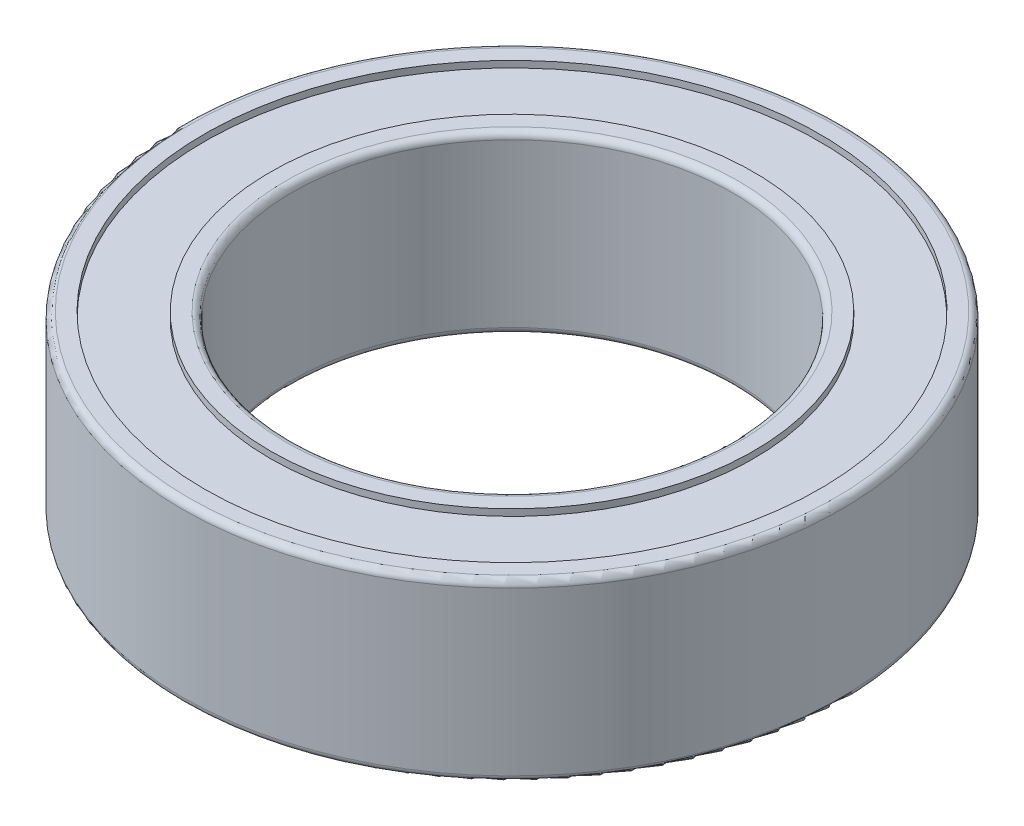
SolidWorks part; units mm, degrees
ref_plane "Plan de face" through (0, 0, 0) normal (0, 0, 1) x (1, 0, 0)
ref_plane "Plan de dessus" through (0, 0, 0) normal (0, 1, 0) x (1, 0, 0)
ref_plane "Plan de droite" through (0, 0, 0) normal (1, 0, 0) x (0, 0, -1)
ref_plane "Plan1" through (0, 0, 0) normal (0, 0, -1) x (-1, 0, 0)
sketch "Esquisse1" plane through (0, 0, 0) normal (0, 0, -1) x (-1, 0, 0)
  line L0 (-5, -1.85) -> (-5, 1.85)
  line L1 (-5.15, 2) -> (-5.5, 2)
  line L2 (-5.5, 2) -> (-5.5, 1.85)
  line L3 (-5.5, 1.85) -> (-7, 1.85)
  line L4 (-7, 1.85) -> (-7, 2)
  line L5 (-7, 2) -> (-7.35, 2)
  line L6 (-7.5, 1.85) -> (-7.5, -1.85)
  line L7 (-7.35, -2) -> (-7, -2)
  line L8 (-7, -2) -> (-7, -1.85)
  line L9 (-7, -1.85) -> (-5.5, -1.85)
  line L10 (-5.5, -1.85) -> (-5.5, -2)
  line L11 (-5.5, -2) -> (-5.15, -2)
  line L12 (0, -2.003) -> (0, 2.0039) construction
  arc A0 (-5.15, -2) -> (-5, -1.85) centre (-5.15, -1.85) ccw
  arc A1 (-5, 1.85) -> (-5.15, 2) centre (-5.15, 1.85) ccw
  arc A2 (-7.35, 2) -> (-7.5, 1.85) centre (-7.35, 1.85) ccw
  arc A3 (-7.5, -1.85) -> (-7.35, -2) centre (-7.35, -1.85) ccw
revolve "Révolution1" add sketch "Esquisse1" angle 360 about L12
